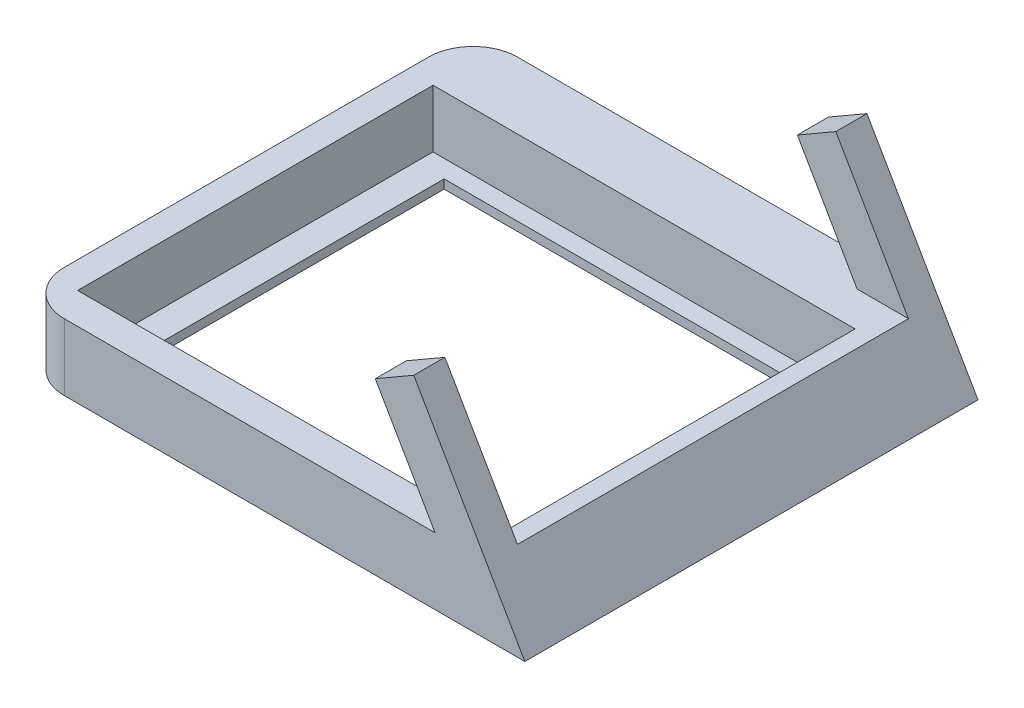
SolidWorks part; units mm, degrees
ref_plane "Ebene vorne" through (0, 0, 0) normal (0, 0, 1) x (1, 0, 0)
ref_plane "Ebene oben" through (0, 0, 0) normal (0, 1, 0) x (1, 0, 0)
ref_plane "Ebene rechts" through (0, 0, 0) normal (1, 0, 0) x (0, 0, -1)
sketch "Skizze6" plane through (0, 0, 0) normal (0, 1, 0) x (1, 0, 0)
  line L1 (0, 0) -> (105, 0)
  line L2 (0, 0) -> (0, 90)
  line L3 (0, 90) -> (105, 90)
  line L4 (105, 0) -> (105, 90)
  dimension "D1" = 90
  dimension "D2" = 105
extrude "Aufsatz-Linear austragen3" add sketch "Skizze6" along normal blind 15
sketch "Skizze7" plane through (0, 15, 0) normal (0, 1, 0) x (1, 0, 0)
  line L0 (0, 90) -> (0, 0) construction
  line L1 (3, 87) -> (101, 87)
  line L2 (3, 87) -> (3, 4)
  line L3 (3, 4) -> (101, 4)
  line L4 (101, 87) -> (101, 4)
  line L5 (105, 90) -> (0, 90) construction
  dimension "D1" = 98
  dimension "D2" = 83
  dimension "D3" = 3
  dimension "D4" = 3
extrude "Schnitt-Linear austragen1" cut sketch "Skizze7" against normal blind 13
sketch "Skizze8" plane through (0, 2, 0) normal (0, 1, 0) x (1, 0, 0)
  line L0 (3, 87) -> (3, 4) construction
  line L1 (5.5, 18) -> (98.5, 18)
  line L2 (5.5, 18) -> (5.5, 84)
  line L3 (5.5, 84) -> (98.5, 84)
  line L4 (98.5, 18) -> (98.5, 84)
  line L6 (3, 4) -> (101, 4) construction
  dimension "D1" = 66
  dimension "D2" = 93
  dimension "D3" = 2.5
  dimension "D4" = 14
extrude "Schnitt-Linear austragen2" cut sketch "Skizze8" against normal blind 13
sketch "Skizze12" plane through (0, 0, 0) normal (0, -1, 0) x (1, 0, 0)
  line L0 (98.5, -18) -> (5.5, -18) construction
  line L1 (5.5, -84) -> (12.5, -84)
  line L2 (5.5, -84) -> (5.5, -18)
  line L3 (5.5, -18) -> (12.5, -18)
  line L4 (12.5, -84) -> (12.5, -18)
  line L6 (98.5, -84) -> (95.5, -84)
  line L7 (98.5, -84) -> (98.5, -18)
  line L8 (98.5, -18) -> (95.5, -18)
  line L9 (95.5, -84) -> (95.5, -18)
  line L10 (95.5, -84) -> (12.5, -84)
  line L11 (95.5, -84) -> (95.5, -83)
  line L12 (95.5, -83) -> (12.5, -83)
  line L13 (12.5, -84) -> (12.5, -83)
  line L14 (95.5, -18) -> (12.5, -18)
  line L15 (95.5, -18) -> (95.5, -19)
  line L16 (95.5, -19) -> (12.5, -19)
  line L17 (12.5, -18) -> (12.5, -19)
  line M7 (5.5, -84) -> (5.5, -18)
  line M8 (5.5, -18) -> (98.5, -18)
  line M9 (98.5, -18) -> (98.5, -84)
  line M10 (98.5, -84) -> (5.5, -84)
  dimension "D1" = 7
  dimension "D2" = 3
  dimension "D3" = 1
  dimension "D4" = 1
extrude "Aufsatz-Linear austragen4" add sketch "Skizze12" against normal up to surface (2 mm away) contours L4 M10 M8 M7 | L9 M10 M9 M8 | L9 L12 L4 M10 | L16 L9 L4 M8 up to face at (52, 2, -51)
sketch "Skizze13" plane through (0, 2, 0) normal (0, 1, 0) x (1, 0, 0)
  line L0 (3, 87) -> (3, 4) construction
  line L1 (101, 4) -> (3, 4)
  line L2 (101, 4) -> (101, 7)
  line L3 (101, 7) -> (3, 7)
  line L4 (3, 4) -> (3, 7)
  line L5 (3, 4) -> (101, 4) construction
  line L6 (101, 87) -> (3, 87) construction
  line L7 (3, 4) -> (6, 4)
  line L8 (3, 4) -> (3, 87)
  line L9 (3, 87) -> (6, 87)
  line L10 (6, 4) -> (6, 87)
  line M6 (3, 87) -> (3, 4)
  line M7 (3, 4) -> (101, 4)
  line M8 (101, 4) -> (101, 87)
  line M9 (101, 87) -> (3, 87)
  dimension "D1" = 3
  dimension "D2" = 3
extrude "Aufsatz-Linear austragen5" add sketch "Skizze13" along direction (0, -1, 0) on the side of the normal up to surface (13 mm away) contours L3 L10 M9 M6 | L10 L3 M7 M6 | L10 L1 L3 M8
sketch "Skizze14" plane through (0, 0, 0) normal (0, -1, 0) x (1, 0, 0)
  line L0 (0, -90) -> (0, 0) construction
  line L1 (0, -19) -> (105, -19)
  line L2 (0, -19) -> (0, 0)
  line L3 (0, 0) -> (105, 0)
  line L4 (105, -19) -> (105, 0)
  line L5 (-4.6084, -51) -> (115.5138, -51) construction
  line L6 (0, -102) -> (105, -102)
  line L7 (105, -83) -> (105, -102)
  line L8 (0, -83) -> (105, -83)
  line L9 (0, -83) -> (0, -102)
extrude "Aufsatz-Linear austragen7" add sketch "Skizze14" along direction (0, 1, 0) on the side against the normal up to surface (2 mm away) contours L6 L7 L8 L9
sketch "Skizze15" plane through (0, 2, 0) normal (0, 1, 0) x (1, 0, 0)
  line L4 (0, 90) -> (105, 90)
  line L5 (105, 90) -> (105, 102)
  line L6 (105, 102) -> (0, 102)
  line L7 (0, 102) -> (0, 90)
  line L8 (0, 90) -> (105, 90)
  line L9 (105, 90) -> (105, 102)
  line L10 (105, 102) -> (0, 102)
  line L11 (0, 102) -> (0, 90)
  dimension "D1" = 0
extrude "Aufsatz-Linear austragen8" add sketch "Skizze15" along normal up to surface (13 mm away) up to face at (53.5, 15, -47)
ref_plane "Ebene1" through (0, 0, 0) normal (1, 0, 0) x (0, 0, -1)
sketch "Skizze21" plane through (0, 0, 0) normal (0, 0, 1) x (1, 0, 0)
  line L0 (105, 15) -> (113.6603, 0)
  line L1 (113.6603, 0) -> (88.6603, 43.3013)
  line L2 (88.6603, 43.3013) -> (80, 38.3013)
  line L3 (80, 38.3013) -> (102.1132, 0)
  line L4 (0, 0) -> (105, 0) construction
  line L5 (102.1132, 0) -> (113.6603, 0)
  line L6 (105, 15) -> (105, 0) construction
  line M8 (105, 15) -> (0, 15)
  dimension "D1" = 10
  dimension "D2" = 30
  dimension "D3" = 50
extrude "Aufsatz-Linear austragen13" add sketch "Skizze21" against normal blind 7 contours L2 L3 L1 M8
ref_plane "Ebene2" through (0, 0, -51) normal (0, 0, -1) x (-1, 0, 0)
mirror "Spiegeln2" about plane through (0, 0, -51) normal (0, 0, -1) of "Aufsatz-Linear austragen13"
sketch "Skizze22" plane through (0, 0, -7) normal (0, 0, -1) x (-1, 0, 0)
  line L3 (-113.6603, 0) -> (-105, 0)
  line L4 (-105, 0) -> (-105, 15)
  line L5 (-105, 15) -> (-113.6603, 0)
  line L6 (-113.6603, 0) -> (-105, 0)
  line L7 (-105, 0) -> (-105, 15)
  line L8 (-105, 15) -> (-113.6603, 0)
  dimension "D1" = 0
extrude "Aufsatz-Linear austragen14" add sketch "Skizze22" along normal up to surface (88 mm away) up to face at (107.8868, 5, -95)
sketch "Skizze28" plane through (0, 0, 0) normal (0, -1, 0) x (1, 0, 0)
  line L0 (-23.8157, -51) -> (23.8157, -51) construction
  circle A38 centre (11.3222, -4.7655) radius 1.25
  circle A39 centre (31.6677, -3.3164) radius 1.25
  circle A40 centre (64.2552, -4.7655) radius 1.25
  circle A41 centre (95.1049, -3.3164) radius 1.25
  circle A47 centre (95.1049, -98.6836) radius 1.25
  circle A48 centre (64.2552, -97.2345) radius 1.25
  circle A49 centre (31.6677, -98.6836) radius 1.25
  circle A50 centre (11.3222, -97.2345) radius 1.25
  circle A51 centre (108.8217, -16.0679) radius 1.25
  circle A52 centre (108.8217, -78.3027) radius 1.25
  circle A53 centre (110.2467, -50.8277) radius 1.25
  circle A60 centre (2.7467, -50.8277) radius 1.25
  circle A61 centre (3.5709, -21.8803) radius 1.25
  circle A62 centre (3.187, -79.048) radius 1.25
  point P28 (4.7078, -22.6355)
  point P29 (3.5709, -21.8803)
  point P30 (3.187, -79.048)
  dimension "D1" = 2.5
extrude "Schnitt-Linear austragen3" cut sketch "Skizze28" against normal blind 2
fillet "Verrundung1" radius 10 2 edges at (0, 7.5, -102) (0, 7.5, 0)
